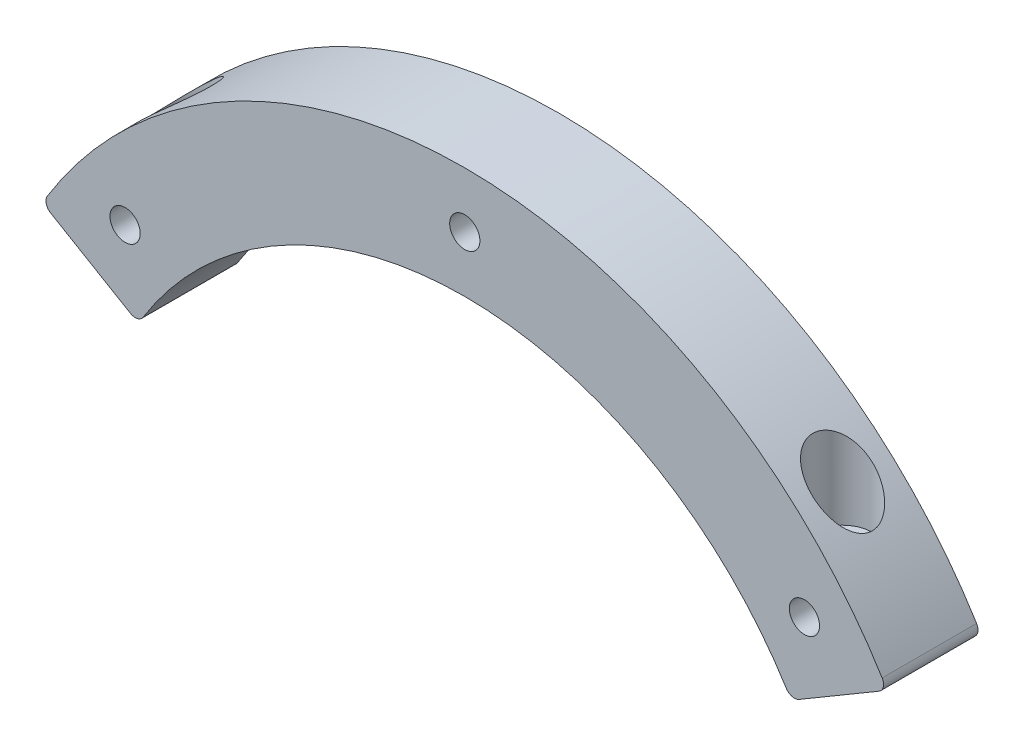
SolidWorks part; units mm, degrees
ref_plane "Ebene vorne" through (0, 0, 0) normal (0, 0, 1) x (1, 0, 0)
ref_plane "Ebene oben" through (0, 0, 0) normal (0, 1, 0) x (1, 0, 0)
ref_plane "Ebene rechts" through (0, 0, 0) normal (1, 0, 0) x (0, 0, -1)
sketch "Skizze1" plane through (0, 0, 0) normal (0, 0, 1) x (1, 0, 0)
  line L0 (-34.5513, 20.3523) -> (-44.7186, 26.3412)
  line L1 (34.5513, 20.3523) -> (44.7186, 26.3412)
  line L2 (0, 0) -> (0, -50000) construction
  line L3 (0, 0) -> (-80.8037, 47.597) construction
  line L4 (0, 0) -> (74.2174, 43.7174) construction
  arc A0 (34.5513, 20.3523) -> (-34.5513, 20.3523) centre (0, 0) ccw
  arc A1 (44.7186, 26.3412) -> (-44.7186, 26.3412) centre (0, 0) ccw
  dimension "D2" = 40.1
  dimension "D3" = 51.9
  dimension "D1" = 119
extrude "Aufsatz-Linear austragen1" add sketch "Skizze1" along normal blind 10
fillet "Verrundung1" radius 1 4 edges at (44.7186, 26.3412, 5) (34.5513, 20.3523, 5) (-34.5513, 20.3523, 5) (-44.7186, 26.3412, 5)
sketch "Skizze2" plane through (0, 0, 10) normal (0, 0, 1) x (1, 0, 0)
  line L0 (0, 0) -> (0, 50000) construction
  circle A0 centre (0, 46) radius 1.6
  circle A1 centre (0, 0) radius 46 construction
  circle A2 centre (35.9642, 28.6805) radius 1.6
  circle A7 centre (-35.9642, 28.6805) radius 1.6
  arc A8 (-44.4636, -11.7894) -> (-45.1755, -8.6701) centre (-44.8467, -10.236) ccw [skipped]
  arc A9 (-18.5052, -42.1136) -> (-21.3879, -40.7254) centre (-19.9587, -41.4446) ccw [skipped]
  arc A10 (18.5052, -42.1136) -> (21.3879, -40.7254) centre (19.9587, -41.4446) ccw [skipped]
  arc A11 (45.1755, -8.6701) -> (44.4636, -11.7894) centre (44.8467, -10.236) ccw [skipped]
  dimension "D1" = 92
  dimension "D2" = 3.2
  dimension "D3" = 7
extrude "Schnitt-Linear austragen1" cut sketch "Skizze2" against normal blind 10
ref_plane "Ebene1" through (0, 51.9, 0) normal (0, 1, 0) x (1, 0, 0)
sketch "Skizze3" plane through (0, 51.9, 0) normal (0, 1, 0) x (1, 0, 0)
  line L0 (0, 0) -> (0, -50000) construction
  line L1 (-44.1924, -5) -> (52.6698, -5) construction
  line L2 (-44.1924, 0) -> (-44.1924, -10) construction
  circle A0 centre (-35, -5) radius 3.15
  circle A1 centre (35, -5) radius 3.15
  dimension "D1" = 6.3
  dimension "D2" = 35
extrude "Schnitt-Linear austragen2" cut sketch "Skizze3" against normal blind 20
